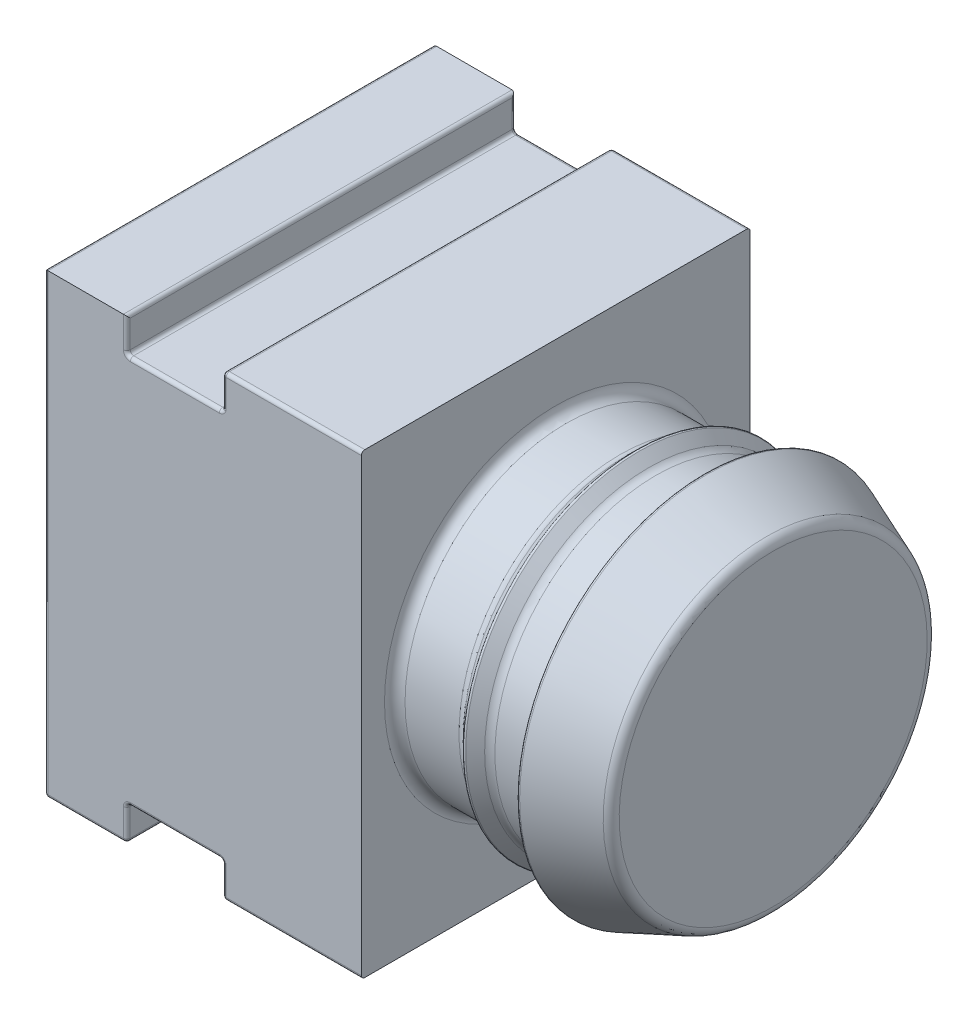
SolidWorks part; units mm, degrees
ref_plane "Front Plane" through (0, 0, 0) normal (0, 0, 1) x (1, 0, 0)
ref_plane "Top Plane" through (0, 0, 0) normal (0, 1, 0) x (1, 0, 0)
ref_plane "Right Plane" through (0, 0, 0) normal (1, 0, 0) x (0, 0, -1)
sketch "Sketch2" plane through (0, 0, 0) normal (0, 1, 0) x (1, 0, 0)
  line L0 (0, -11.35) -> (0, 11.35)
  line L1 (0, 11.35) -> (-18.5, 11.35)
  line L2 (-18.5, 11.35) -> (-18.5, -11.35)
  line L3 (-18.5, -11.35) -> (0, -11.35)
  circle A0 centre (-12.7, 0) radius 3.175
  point P4 (0, 0)
  point P10 (-18.5, 0)
  dimension "D3" = 6.35
  dimension "D4" = 5.8
  dimension "D1" = 22.7
  dimension "D2" = 12.7
extrude "Boss-Extrude2" add sketch "Sketch2" along normal mid plane 22.7
sketch "Sketch3" plane through (0, 0, 0) normal (0, 0, 1) x (1, 0, 0)
  line L1 (0, 11.35) -> (0, -11.35) construction
  line L4 (0, 0) -> (0, 9.4)
  line L13 (12.7, 9.4) -> (12.7, 0)
  line L14 (12.7, 0) -> (0, 0)
  line L15 (12.7, 9.4) -> (8.7, 11)
  line L16 (8.7, 11) -> (8.7, 9.4)
  line L23 (0, 9.4) -> (4, 9.4)
  line L25 (5.6, 9.4) -> (4.8, 10.2)
  line L26 (4.8, 10.2) -> (4, 9.4)
  line L27 (5.6, 9.4) -> (8.7, 9.4)
  line L29 (4.8, 10.2) -> (4.8, 9.4) construction
  line L30 (5.6, 9.4) -> (4.8, 9.4) construction
  point P14 (4.8, 9.4)
  dimension "D1" = 12.7
  dimension "D2" = 9.4
  dimension "D3" = 4
  dimension "D4" = 1.6
  dimension "D5" = 7.9
  dimension "D6" = 0.8
revolve "Revolve1" add sketch "Sketch3" angle 360 about L14
sketch "Sketch18" plane through (12.7, 0, 0) normal (1, 0, 0) x (0, 0, -1)
  circle A0 centre (0, 0) radius 2.4
  dimension "D1" = 4.8
sketch "Sketch12" plane through (0, -11.35, 0) normal (0, -1, 0) x (1, 0, 0)
  circle A0 centre (-12.7, 0) radius 3.175
  dimension "D1" = 6.35
extrude "Boss-Extrude3" add sketch "Sketch12" against normal blind 22.7
sketch "Sketch13" plane through (0, -11.35, 0) normal (0, -1, 0) x (1, 0, 0)
  line L1 (0, 11.35) -> (-18.5, 11.35)
  line L2 (0, 11.35) -> (0, -11.35)
  line L3 (0, -11.35) -> (-18.5, -11.35)
  line L4 (-18.5, 11.35) -> (-18.5, -11.35)
extrude "Boss-Extrude4" add sketch "Sketch13" along normal blind 2
mirror "Mirror1" about plane through (0, 0, 0) normal (0, 1, 0) of "Boss-Extrude4"
sketch "Sketch15" plane through (0, 0, -11.35) normal (0, 0, -1) x (-1, 0, 0)
  line L1 (8.1, 13.35) -> (13.7, 13.35)
  line L2 (8.1, 13.35) -> (8.1, 11.35)
  line L3 (8.1, 11.35) -> (13.7, 11.35)
  line L4 (13.7, 13.35) -> (13.7, 11.35)
  line L5 (18.5, 13.35) -> (0, 13.35) construction
  line L10 (18.5, 13.35) -> (18.5, -13.35) construction
  line L11 (0, 0) -> (50000, 0) construction
  line L12 (13.7, -13.35) -> (13.7, -11.35)
  line L13 (8.1, -11.35) -> (13.7, -11.35)
  line L14 (8.1, -13.35) -> (8.1, -11.35)
  line L15 (8.1, -13.35) -> (13.7, -13.35)
  point P8 (18.5, 0)
  point P14 (8.1, 12.35)
  dimension "D1" = 2
  dimension "D3" = 4.8
  dimension "D4" = 5.6
extrude "Cut-Extrude1" cut sketch "Sketch15" against normal through all
fillet "Fillet1" radius 0.1 2 edges at (4.8, 10.2, 0) (8.7, 11, 0)
fillet "Fillet2" radius 0.6 5 edges at (8.7, 9.4, 0) (5.6, 9.4, 0) (4, 9.4, 0) (0, 9.4, 0) (12.7, 9.4, 0)
fillet "Fillet5" radius 0.2 28 edges at (-4.05, -13.35, 11.35) (-18.5, -13.35, 0) (-16.1, -13.35, -11.35) (-18.5, 13.35, 0) (-16.1, -13.35, 11.35) (-4.05, -13.35, -11.35) (-8.1, 12.35, 11.35) (-8.1, 11.35, 0) (-8.1, 13.35, 0) (-13.7, 12.35, 11.35) (-13.7, 13.35, 0) (-10.9, 11.35, 11.35) (-13.7, 11.35, 0) (-8.1, 12.35, -11.35) (-10.9, 11.35, -11.35) (-13.7, 12.35, -11.35) (-13.7, -13.35, 0) (-8.1, -12.35, 11.35) (-8.1, -13.35, 0) (-10.9, -11.35, 11.35) (-8.1, -11.35, 0) (-13.7, -12.35, 11.35) (-13.7, -11.35, 0) (-13.7, -12.35, -11.35) (-10.9, -11.35, -11.35) (-8.1, -12.35, -11.35) (-18.5, 0, 11.35) (-18.5, 0, -11.35)
